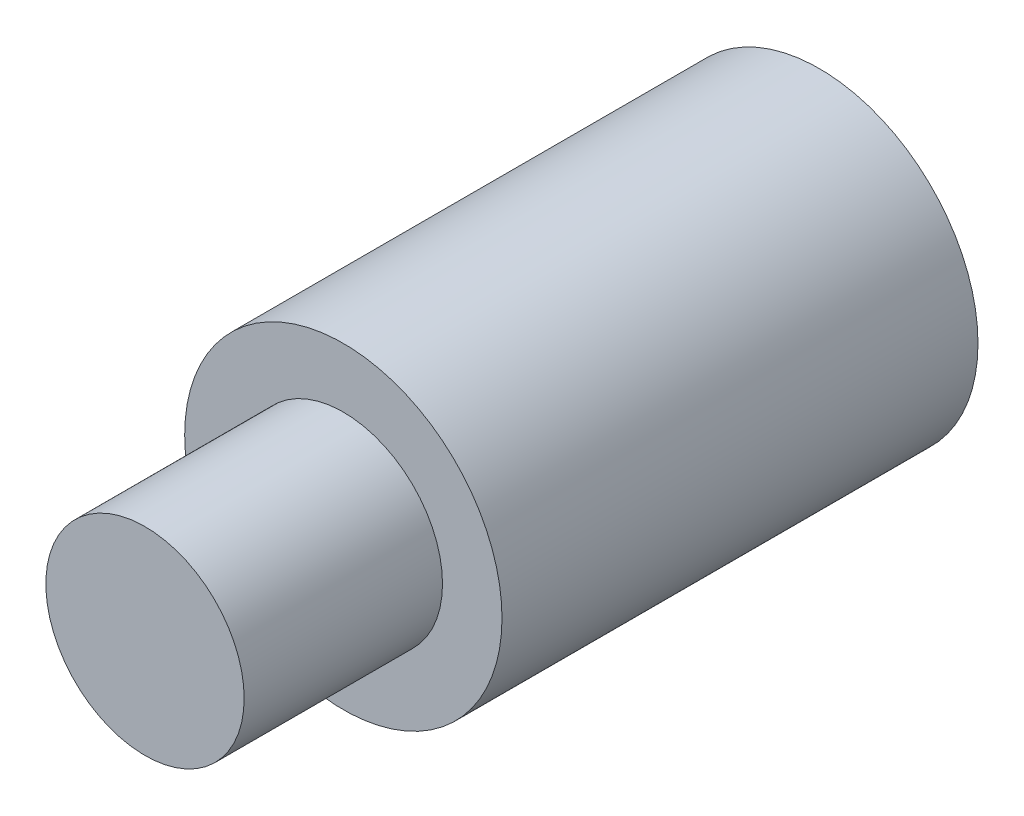
SolidWorks part; units mm, degrees
ref_plane "Plan de face" through (0, 0, 0) normal (0, 0, 1) x (1, 0, 0)
ref_plane "Plan de dessus" through (0, 0, 0) normal (0, 1, 0) x (1, 0, 0)
ref_plane "Plan de droite" through (0, 0, 0) normal (1, 0, 0) x (0, 0, -1)
sketch "Esquisse1" plane through (0, 0, 0) normal (0, 0, 1) x (1, 0, 0)
  circle A0 centre (0, 0) radius 2.5
extrude "Boss.-Extru.1" add sketch "Esquisse1" along normal blind 5
sketch "Esquisse3" plane through (0, 0, 0) normal (0, 0, 1) x (1, 0, 0)
  circle A0 centre (0, 0) radius 4
extrude "Boss.-Extru.2" add sketch "Esquisse3" against normal blind 12
